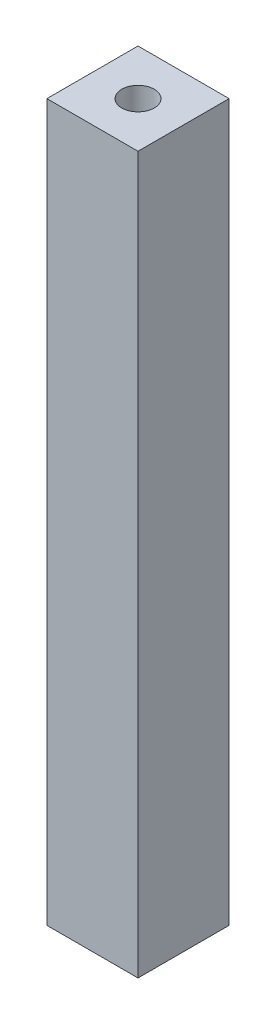
SolidWorks part; units mm, degrees
ref_plane "Front Plane" through (0, 0, 0) normal (0, 0, 1) x (1, 0, 0)
ref_plane "Top Plane" through (0, 0, 0) normal (0, 1, 0) x (1, 0, 0)
ref_plane "Right Plane" through (0, 0, 0) normal (1, 0, 0) x (0, 0, -1)
sketch "Sketch1" plane through (0, 0, 0) normal (0, 1, 0) x (1, 0, 0)
  line L0 (0, 3.5) -> (-3.5, 3.5)
  line L1 (-3.5, 3.5) -> (-3.5, -3.5)
  line L2 (-3.5, -3.5) -> (3.5, -3.5)
  line L3 (3.5, -3.5) -> (3.5, 3.5)
  line L4 (3.5, 3.5) -> (0, 3.5)
extrude "Boss-Extrude1" add sketch "Sketch1" along normal blind 55
sketch "Sketch2" plane through (0, 55, 0) normal (0, 1, 0) x (1, 0, 0)
  circle A0 centre (0, 0) radius 1.25
extrude "Cut-Extrude1" cut sketch "Sketch2" against normal blind 12 contours A0
sketch "Sketch3" plane through (0, 0, 0) normal (0, -1, 0) x (1, 0, 0)
  circle A0 centre (0, 0) radius 1.25
extrude "Cut-Extrude2" cut sketch "Sketch3" against normal blind 12
